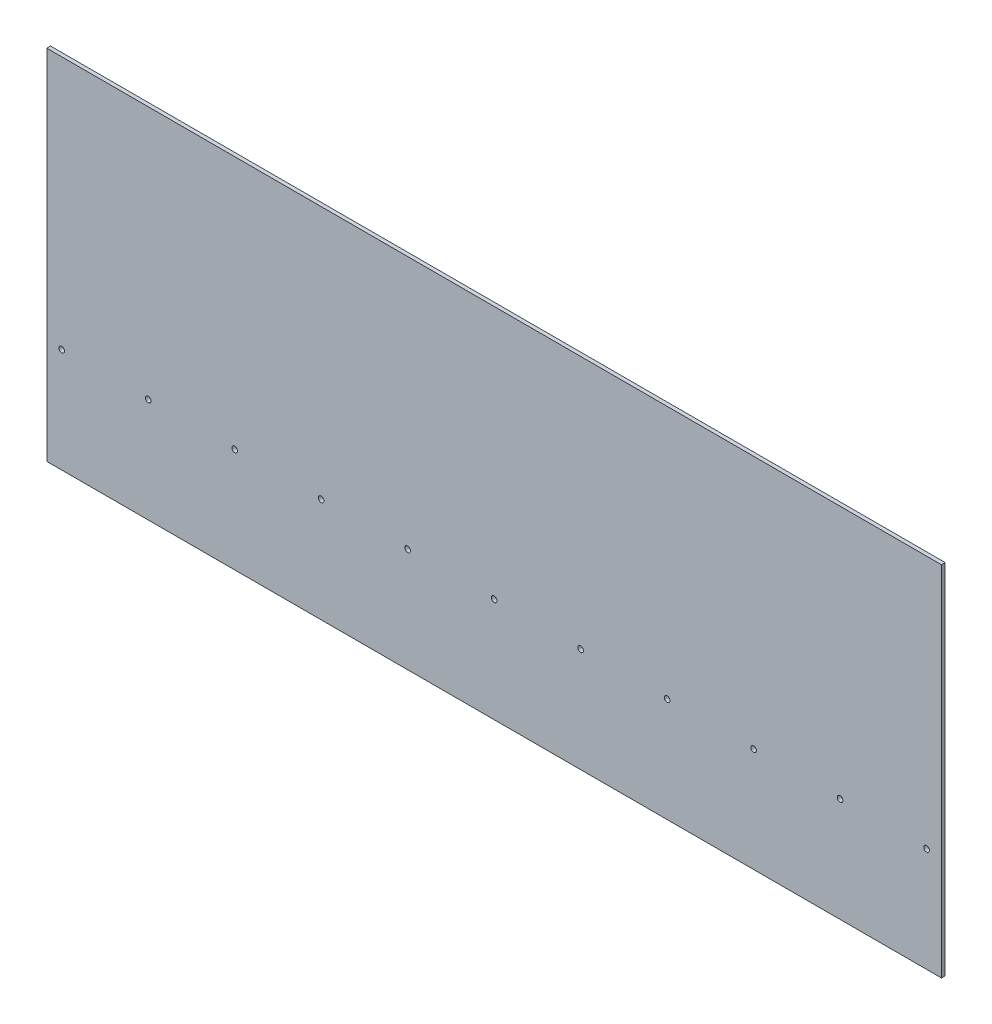
SolidWorks part; units mm, degrees
ref_plane "Front Plane" through (0, 0, 0) normal (0, 0, 1) x (1, 0, 0)
ref_plane "Top Plane" through (0, 0, 0) normal (0, 1, 0) x (1, 0, 0)
ref_plane "Right Plane" through (0, 0, 0) normal (1, 0, 0) x (0, 0, -1)
sketch "Sketch1" plane through (0, 0, 0) normal (0, 0, 1) x (1, 0, 0)
  line L1 (-381, 152.4) -> (381, 152.4)
  line L2 (-381, 152.4) -> (-381, -152.4)
  line L3 (-381, -152.4) -> (381, -152.4)
  line L4 (381, 152.4) -> (381, -152.4)
  line L5 (-381, 152.4) -> (381, -152.4) construction
  line L6 (-381, -152.4) -> (381, 152.4) construction
  point P0 (0, 0)
  dimension "D1" = 304.8
  dimension "D2" = 762
extrude "Boss-Extrude1" add sketch "Sketch1" along normal blind 3.175
sketch "Sketch2" plane through (0, 0, 3.175) normal (0, 0, 1) x (1, 0, 0)
  line L0 (-381, -63.5) -> (381, -63.5) construction
  line L1 (-381, 152.4) -> (-381, -152.4) construction
  line L2 (381, -152.4) -> (381, 152.4) construction
  line L4 (-381, -152.4) -> (381, -152.4) construction
  circle A0 centre (-368.3, -63.5) radius 2.413
  circle A1 centre (-294.64, -63.5) radius 2.413
  circle A2 centre (-220.98, -63.5) radius 2.413
  circle A3 centre (-147.32, -63.5) radius 2.413
  circle A4 centre (-73.66, -63.5) radius 2.413
  circle A5 centre (0, -63.5) radius 2.413
  circle A6 centre (73.66, -63.5) radius 2.413
  circle A7 centre (147.32, -63.5) radius 2.413
  circle A8 centre (220.98, -63.5) radius 2.413
  circle A9 centre (294.64, -63.5) radius 2.413
  circle A10 centre (368.3, -63.5) radius 2.413
  dimension "D2" = 4.826
  dimension "D1" = 88.9
  dimension "D3" = 12.7
  dimension "D4" = 11
extrude "Cut-Extrude1" cut sketch "Sketch2" against normal through all
